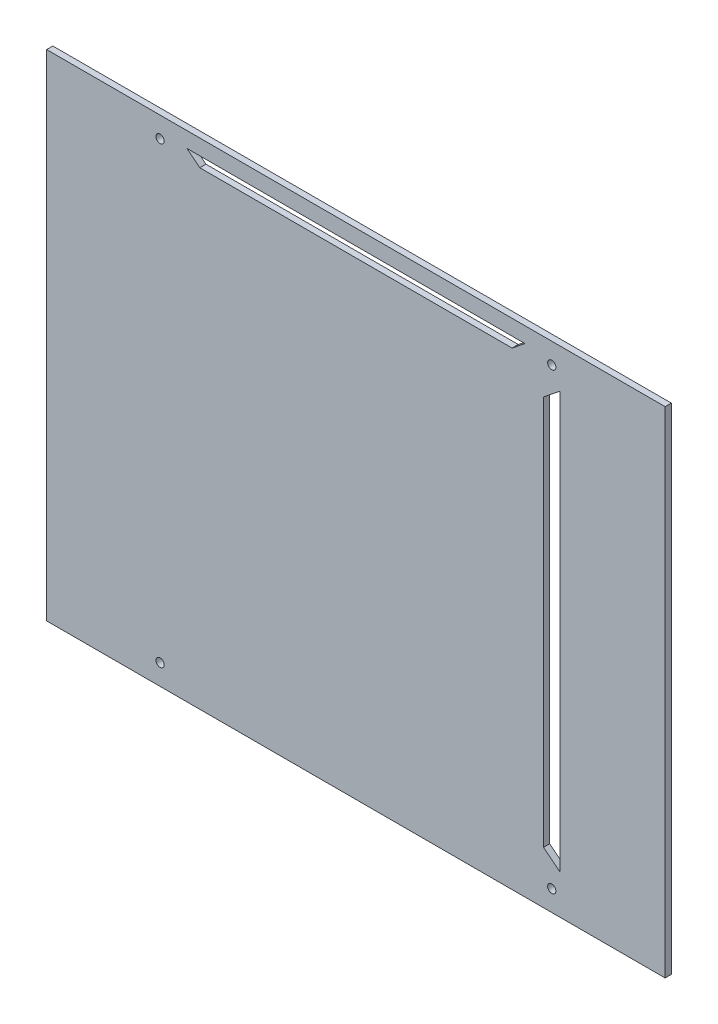
SolidWorks part; units mm, degrees
ref_plane "Front Plane" through (0, 0, 0) normal (0, 0, 1) x (1, 0, 0)
ref_plane "Top Plane" through (0, 0, 0) normal (0, 1, 0) x (1, 0, 0)
ref_plane "Right Plane" through (0, 0, 0) normal (1, 0, 0) x (0, 0, -1)
sketch "Sketch1" plane through (0, 0, 0) normal (0, 0, 1) x (1, 0, 0)
  line L0 (0, 0) -> (-206.9982, 0) construction
  line L1 (150, -120) -> (-150, -120)
  line L2 (150, -120) -> (150, 120)
  line L3 (150, 120) -> (-150, 120)
  line L4 (-150, -120) -> (-150, 120)
  line L5 (150, -120) -> (-150, 120) construction
  line L6 (150, 120) -> (-150, -120) construction
  line L7 (137.5, -110) -> (-137.5, -110) construction
  line L8 (137.5, -110) -> (137.5, 110) construction
  line L9 (137.5, 110) -> (-137.5, 110) construction
  line L10 (-137.5, -110) -> (-137.5, 110) construction
  line L11 (137.5, -110) -> (-137.5, 110) construction
  line L12 (137.5, 110) -> (-137.5, -110) construction
  line L13 (99, 101) -> (99, -101)
  line L14 (91, 94.6) -> (91, -94.6)
  line L15 (99, 101) -> (91, 94.6)
  line L16 (99, -101) -> (91, -94.6)
  line L17 (82, 112.5) -> (-82, 112.5)
  line L18 (95, 94.6) -> (95, -94.6) construction
  line L19 (-82, 112.5) -> (-75.75, 107.5)
  line L20 (82, 112.5) -> (75.75, 107.5)
  line L21 (137.5, 112.5) -> (-137.5, 112.5) construction
  line L22 (75.75, 107.5) -> (-75.75, 107.5)
  circle A0 centre (-95, 110) radius 2
  circle A1 centre (95, 110) radius 2
  circle A2 centre (95, -110) radius 2
  circle A3 centre (-95, -110) radius 2
  point P0 (0, 0)
  point P5 (0, 0)
  dimension "D4" = 4
  dimension "D5" = 4
  dimension "D1" = 300
  dimension "D2" = 240
  dimension "D3" = 10
  dimension "D6" = 55
  dimension "D7" = 55
  dimension "D8" = 9
  dimension "D9" = 8
  dimension "D10" = 55
  dimension "D11" = 9
  dimension "D14" = 13
  dimension "D15" = 13
  dimension "D13" = 2.5
  dimension "D12" = 2.5
  dimension "D16" = 4
extrude "Boss-Extrude1" add sketch "Sketch1" along normal blind 3
